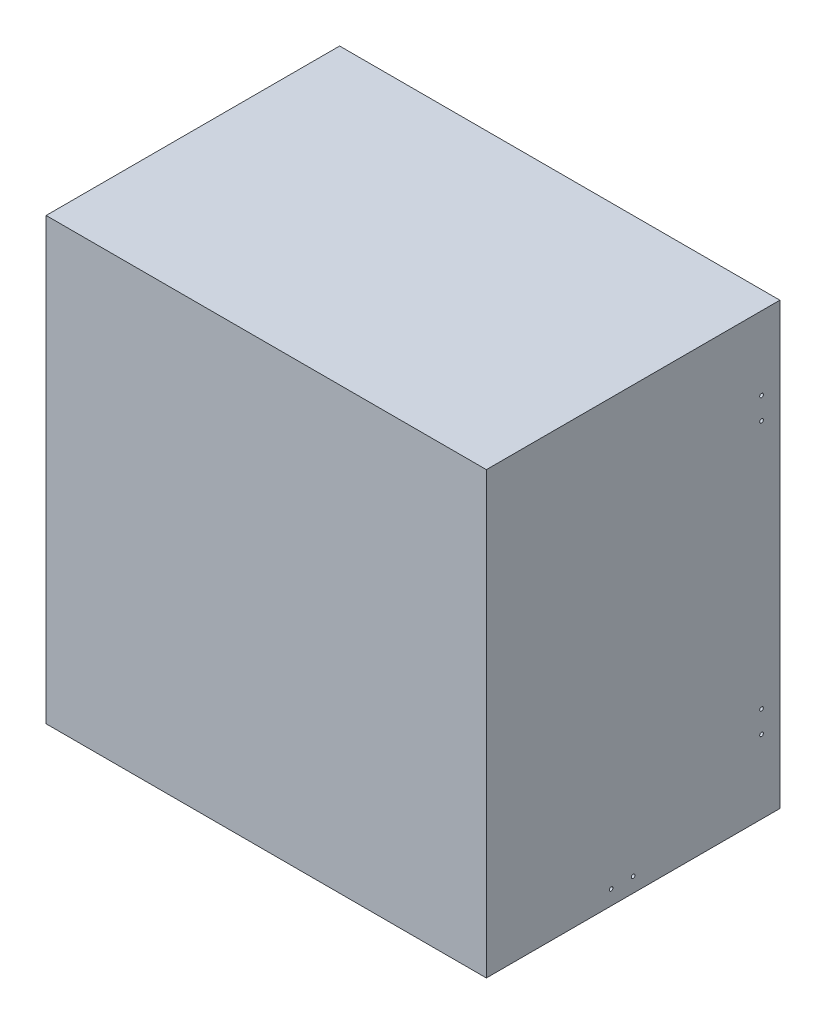
SolidWorks part; units mm, degrees
ref_plane "Front Plane" through (0, 0, 0) normal (0, 0, 1) x (1, 0, 0)
ref_plane "Top Plane" through (0, 0, 0) normal (0, 1, 0) x (1, 0, 0)
ref_plane "Right Plane" through (0, 0, 0) normal (1, 0, 0) x (0, 0, -1)
sketch "Sketch2" plane through (0, 0, 0) normal (0, 1, 0) x (1, 0, 0)
  line L1 (-300, 200) -> (300, 200)
  line L2 (-300, 200) -> (-300, -200)
  line L3 (-300, -200) -> (300, -200)
  line L4 (300, 200) -> (300, -200)
  line L5 (-300, 200) -> (300, -200) construction
  line L6 (-300, -200) -> (300, 200) construction
  point P0 (0, 0)
  dimension "D1" = 600
  dimension "D2" = 400
extrude "Boss-Extrude1" add sketch "Sketch2" along normal blind 600
shell "Shell1" thickness 50
sketch "Sketch3" plane through (-300, 0, 0) normal (-1, 0, 0) x (0, 0, 1)
  line L0 (-200, 600) -> (-200, 0) construction
  line L1 (-200, 0) -> (200, 0) construction
  circle A0 centre (-175, 100) radius 2.5
  circle A1 centre (-175, 130) radius 2.5
  circle A2 centre (-175, 470) radius 2.5
  circle A3 centre (-175, 500) radius 2.5
  dimension "D1" = 5
  dimension "D2" = 25
  dimension "D3" = 25
  dimension "D4" = 25
  dimension "D5" = 25
  dimension "D7" = 30
  dimension "D8" = 340
  dimension "D9" = 30
  dimension "D6" = 100
extrude "Cut-Extrude1" cut sketch "Sketch3" against normal through all
sketch "Sketch4" plane through (0, 0, 0) normal (1, 0, 0) x (0, 0, -1)
  line L0 (-200, 0) -> (200, 0) construction
  circle A0 centre (-105, 130) radius 2.5
  circle A1 centre (145, 130) radius 2.5
  circle A2 centre (175, 130) radius 2.5 construction
  dimension "D1" = 250
  dimension "D2" = 130
  dimension "D3" = 130
  dimension "D4" = 5
  dimension "D5" = 5
  dimension "D6" = 30
extrude "Cut-Extrude2" cut sketch "Sketch4" against normal mid plane 550
pattern_linear "LPattern1" count 8 spacing 50 along (0, 1, 0) of "Cut-Extrude2"
sketch "Sketch5" plane through (-300, 0, 0) normal (-1, 0, 0) x (0, 0, 1)
  line L1 (-200, 600) -> (-200, 0) construction
  line L2 (-200, 0) -> (200, 0) construction
  circle A0 centre (0, 20) radius 2.5
  circle A1 centre (30, 20) radius 2.5
  dimension "D1" = 30
  dimension "D2" = 5
  dimension "D4" = 20
  dimension "D3" = 200
extrude "Cut-Extrude3" cut sketch "Sketch5" against normal through all
